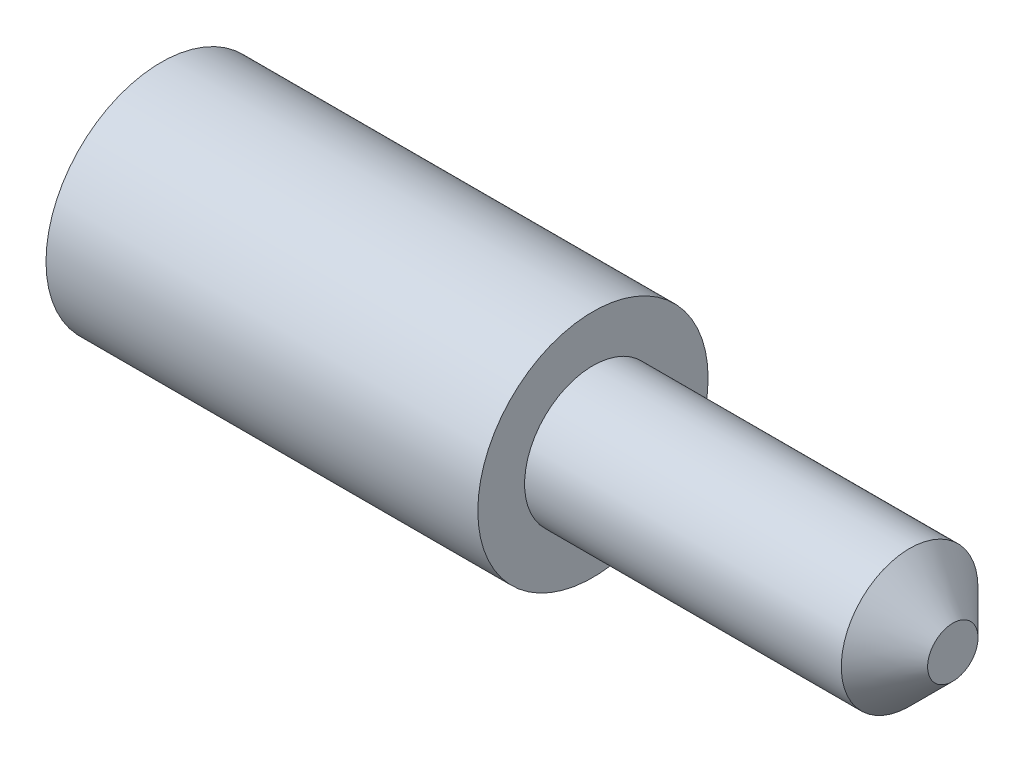
SolidWorks part; units mm, degrees
material "AISI 1020"
ref_plane "Спереди" through (0, 0, 0) normal (0, 0, 1) x (1, 0, 0)
ref_plane "Сверху" through (0, 0, 0) normal (0, 1, 0) x (1, 0, 0)
ref_plane "Справа" through (0, 0, 0) normal (1, 0, 0) x (0, 0, -1)
sketch "Эскиз1" plane through (0, 0, 0) normal (1, 0, 0) x (0, 0, -1)
  circle A0 centre (0, 0) radius 8 construction
  circle A1 centre (0, 0) radius 8
extrude "Бобышка-Вытянуть1" add sketch "Эскиз1" against normal blind 30
sketch "Эскиз2" plane through (0, 0, 0) normal (1, 0, 0) x (0, 0, -1)
  circle A4 centre (0, 0) radius 4.75
  circle A5 centre (0, 0) radius 4.75
  dimension "D1" = 0.25
extrude "Бобышка-Вытянуть2" add sketch "Эскиз2" along normal blind 25
chamfer "Фаска1" distance 3 angle 45 1 edges at (25, 0, -4.75)
